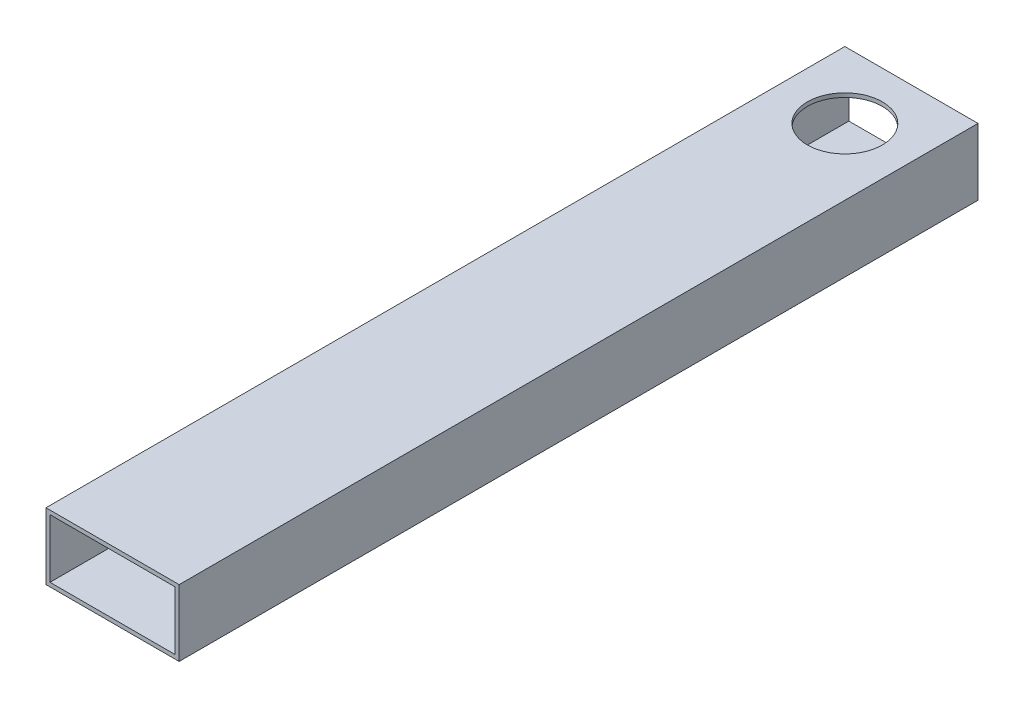
SolidWorks part; units mm, degrees
ref_plane "Front Plane" through (0, 0, 0) normal (0, 0, 1) x (1, 0, 0)
ref_plane "Top Plane" through (0, 0, 0) normal (0, 1, 0) x (1, 0, 0)
ref_plane "Right Plane" through (0, 0, 0) normal (1, 0, 0) x (0, 0, -1)
sketch "Sketch1" plane through (0, 0, 0) normal (0, 0, 1) x (1, 0, 0)
  line L1 (0, 0) -> (-50.8, 0)
  line L2 (0, 0) -> (0, -25.4)
  line L3 (0, -25.4) -> (-50.8, -25.4)
  line L4 (-50.8, 0) -> (-50.8, -25.4)
  dimension "D1" = 50.8
  dimension "D2" = 25.4
extrude "Extrude-Thin1" add sketch "Sketch1" along normal blind 304.8 thin thin type one direction reverse wall 1.524
sketch "Sketch2" plane through (0, 0, 0) normal (0, 1, 0) x (1, 0, 0)
  line L0 (0, 0) -> (-50.8, 0) construction
  circle A0 centre (-25.4, -25.4) radius 14.2875
  dimension "D1" = 28.575
  dimension "D2" = 25.4
extrude "Cut-Extrude2" cut sketch "Sketch2" against normal blind 25.4
